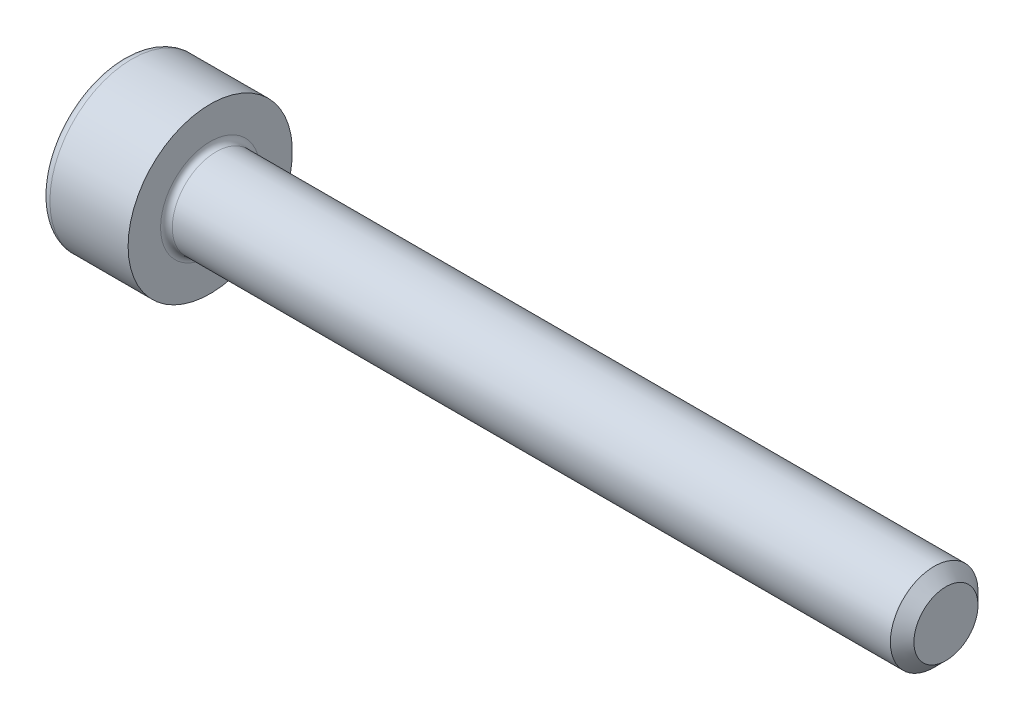
SolidWorks part; units mm, degrees
ref_plane "Спереди" through (0, 0, 0) normal (0, 0, 1) x (1, 0, 0)
ref_plane "Сверху" through (0, 0, 0) normal (0, 1, 0) x (1, 0, 0)
ref_plane "Справа" through (0, 0, 0) normal (1, 0, 0) x (0, 0, -1)
sketch "Sketch1" plane through (0, 0, 0) normal (0, 0, 1) x (1, 0, 0)
  line L0 (0, 0) -> (1.4887, 0)
  line L1 (1.4887, 0) -> (1.4887, 1.3957)
  line L2 (1.4887, 1.3957) -> (0, 1.3957)
  line L3 (0, 1.3957) -> (0, 0)
  line L4 (1.4887, 0) -> (13.9887, 0)
  line L5 (13.9887, 0) -> (13.9887, 0.7444)
  line L6 (13.9887, 0.7444) -> (1.4887, 0.7444)
  dimension "D1" = 12.5
revolve "Revolve1" add sketch "Sketch1" angle 360 about L0
fillet "Fillet1" radius 0.1 1 edges at (1.4887, 0, 0.7444)
fillet "Fillet2" radius 0.16 1 edges at (0, 0, 1.3957)
chamfer "Chamfer1" distance 0.2 angle 45 1 edges at (13.9887, 0, 0.7444)
sketch "Sketch2" plane through (0, 0, 0) normal (-1, 0, 0) x (0, 0, 1)
  line L1 (0, 0.8776) -> (-0.76, 0.4388)
  line L2 (-0.76, 0.4388) -> (-0.76, -0.4388)
  line L3 (-0.76, -0.4388) -> (0, -0.8776)
  line L4 (0, -0.8776) -> (0.76, -0.4388)
  line L5 (0.76, -0.4388) -> (0.76, 0.4388)
  line L6 (0.76, 0.4388) -> (0, 0.8776)
  circle A0 centre (0, 0) radius 0.76 construction
extrude "Extrude1" cut sketch "Sketch2" against normal blind 0.7
